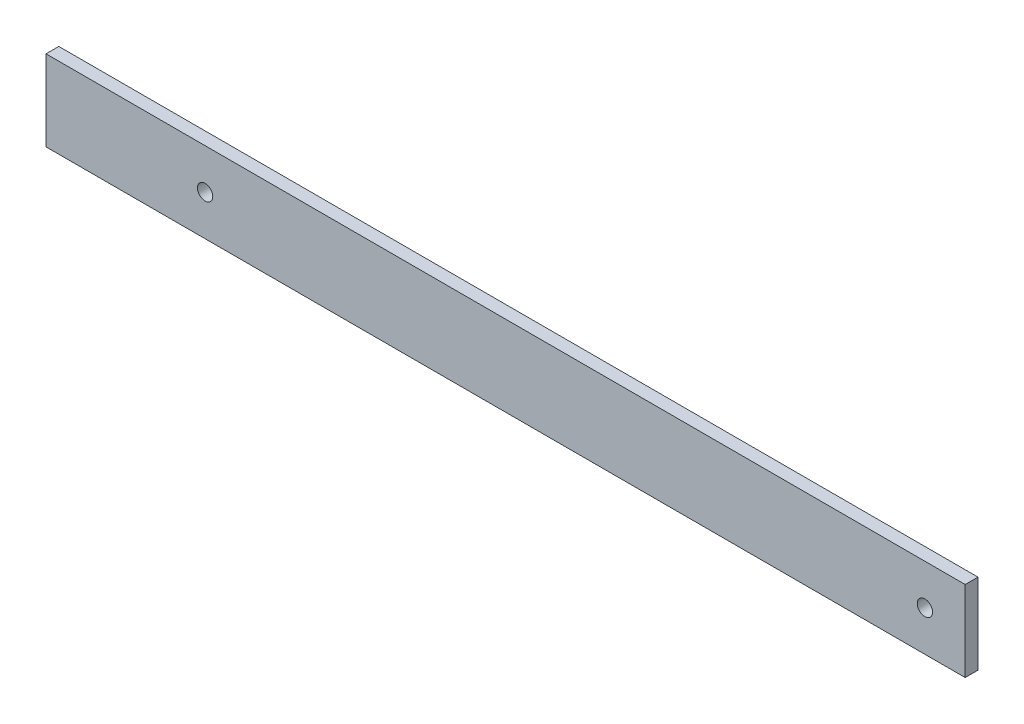
SolidWorks part; units mm, degrees
ref_plane "Front Plane" through (0, 0, 0) normal (0, 0, 1) x (1, 0, 0)
ref_plane "Top Plane" through (0, 0, 0) normal (0, 1, 0) x (1, 0, 0)
ref_plane "Right Plane" through (0, 0, 0) normal (1, 0, 0) x (0, 0, -1)
sketch "Sketch2" plane through (0, 0, 0) normal (0, 0, 1) x (1, 0, 0)
  line L1 (0, 0) -> (228.06, 0)
  line L2 (0, 0) -> (0, 20)
  line L3 (0, 20) -> (228.06, 20)
  line L4 (228.06, 0) -> (228.06, 20)
  dimension "D1" = 228.06
  dimension "D2" = 20
extrude "Boss-Extrude1" add sketch "Sketch2" against normal blind 3.175
hole_wizard "#6 Clearance Hole1" positions "Sketch8" profile "Sketch5" hole size "#6" standard "ANSI Inch"
sketch "Sketch8" plane through (0, 0, 0) normal (0, 0, 1) x (1, 0, 0)
  line L1 (26.3, 20) -> (26.3, 0) construction
  line L2 (228.06, 20) -> (0, 20) construction
  line L3 (0, 0) -> (228.06, 0) construction
  line L4 (29.475, 20) -> (29.475, 0) construction
  line L6 (204.885, 20) -> (204.885, 0) construction
  line L8 (208.06, 20) -> (208.06, 0) construction
  line L10 (228.06, 0) -> (228.06, 20) construction
  line L11 (0, 20) -> (0, 0) construction
  line L12 (0, 10) -> (228.06, 10) construction
  line L14 (114.885, 20) -> (114.885, 0) construction
  point P0 (218.06, 10)
  point P3 (39.475, 10)
  dimension "D1" = 23.175
  dimension "D2" = 3.175
  dimension "D3" = 26.3
  dimension "D4" = 3.175
  dimension "D5" = 10
  dimension "D6" = 10
  dimension "D7" = 90
sketch "Sketch5" plane through (218.06, 10, 0) normal (1, 0, 0) x (0, -1, 0)
  line L0 (0, 0) -> (0, 4.3148)
  line L1 (0, 4.3148) -> (1.8986, 3.174)
  line L2 (1.8986, 3.174) -> (1.8986, 0)
  line L5 (1.8986, 0) -> (0, 0)
  line L10 (0, 4.3148) -> (-1.8987, 3.174) construction
  line L11 (0, -6.35) -> (0, 107.95) construction
  dimension "Hole Dia." = 3.7973
  dimension "Hole Depth" = 3.174
  dimension "Drill Angle" = 118
